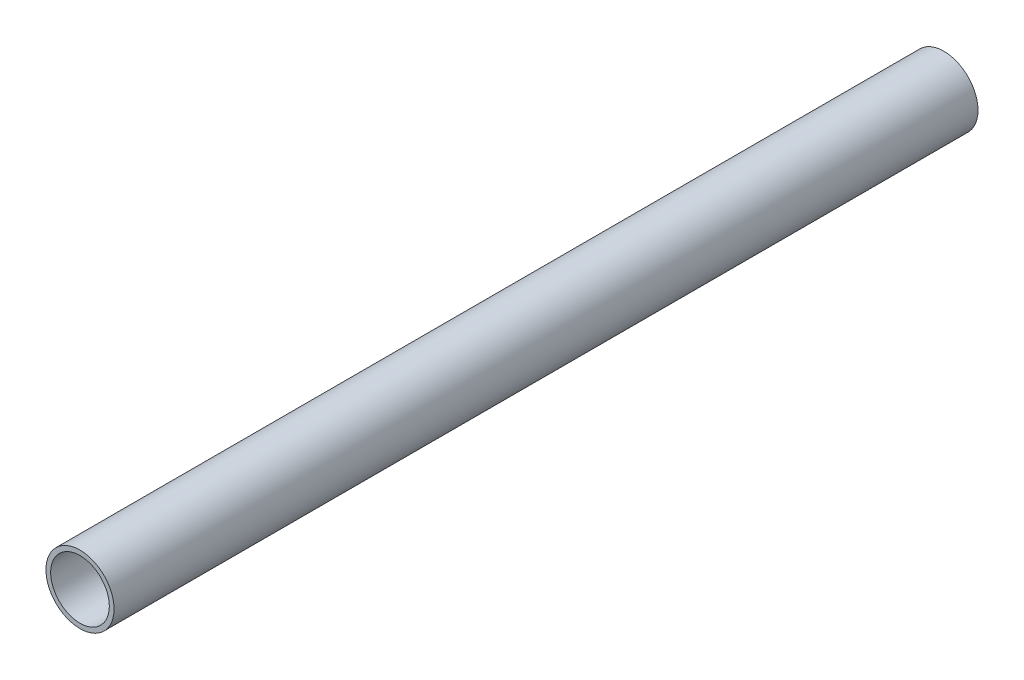
SolidWorks part; units mm, degrees
ref_plane "前视基准面" through (0, 0, 0) normal (0, 0, 1) x (1, 0, 0)
ref_plane "上视基准面" through (0, 0, 0) normal (0, 1, 0) x (1, 0, 0)
ref_plane "右视基准面" through (0, 0, 0) normal (1, 0, 0) x (0, 0, -1)
sketch "草图1" plane through (0, 0, 0) normal (0, 0, 1) x (1, 0, 0)
  circle A0 centre (0, 0) radius 7.55
  circle A1 centre (0, 0) radius 6.5
  dimension "D1" = 15.1
  dimension "D2" = 13
extrude "凸台-拉伸1" add sketch "草图1" along normal blind 191.55
